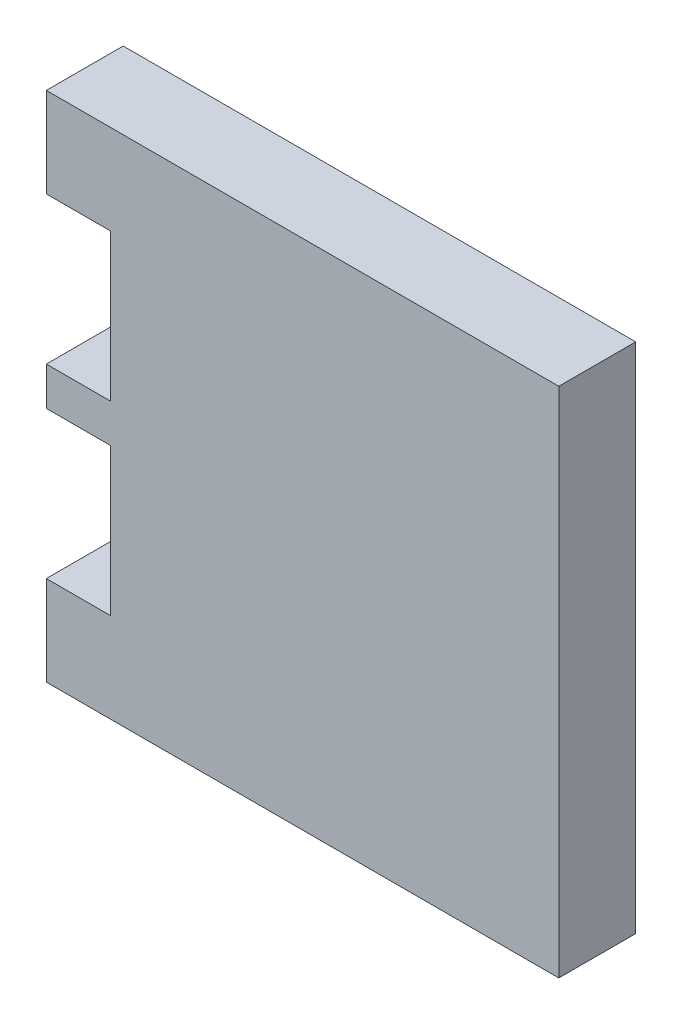
SolidWorks part; units mm, degrees
material "Plain Carbon Steel"
ref_plane "Front" through (0, 0, 0) normal (0, 0, 1) x (1, 0, 0)
ref_plane "Top" through (0, 0, 0) normal (0, 1, 0) x (1, 0, 0)
ref_plane "Right" through (0, 0, 0) normal (1, 0, 0) x (0, 0, -1)
sketch "Sketch1" plane through (0, 0, 0) normal (0, 0, 1) x (1, 0, 0)
  line L1 (-25.7556, 29.8071) -> (19.2444, 29.8071)
  line L2 (-25.7556, 29.8071) -> (-25.7556, -10.1929)
  line L3 (-25.7556, -10.1929) -> (19.2444, -10.1929)
  line L4 (19.2444, 29.8071) -> (19.2444, -10.1929)
  dimension "D1" = 45
  dimension "D2" = 40
extrude "Boss-Extrude1" add sketch "Sketch1" along normal blind 6 contours L2 L1 L4 L3
sketch "Sketch2" plane through (0, 0, 6) normal (0, 0, 1) x (1, 0, 0)
  line L0 (-25.7556, 29.8071) -> (-25.7556, -10.1929) construction
  line L1 (-25.7556, 29.8071) -> (-20.7556, 29.8071)
  line L2 (-25.7556, 29.8071) -> (-25.7556, 22.8071)
  line L3 (-25.7556, 22.8071) -> (-20.7556, 22.8071)
  line L4 (-20.7556, 29.8071) -> (-20.7556, 22.8071)
  line L5 (-25.7556, 22.8071) -> (-20.7556, 22.8071)
  line L6 (-25.7556, 22.8071) -> (-25.7556, 11.3071)
  line L7 (-25.7556, 11.3071) -> (-20.7556, 11.3071)
  line L8 (-20.7556, 22.8071) -> (-20.7556, 11.3071)
  line L9 (-25.7556, 8.3071) -> (-20.7556, 8.3071)
  line L10 (-25.7556, 8.3071) -> (-25.7556, -3.1929)
  line L11 (-25.7556, -3.1929) -> (-20.7556, -3.1929)
  line L12 (-20.7556, 8.3071) -> (-20.7556, -3.1929)
  line M4 (-25.7556, 29.8071) -> (-25.7556, -10.1929)
  dimension "D1" = 7
  dimension "D2" = 5
  dimension "D3" = 11.5
  dimension "D4" = 3
  dimension "D5" = 11.5
extrude "Cut-Extrude1" cut sketch "Sketch2" against normal blind 6 contours L8 L3 L7 M4 | L12 L9 L11 M4
sketch "Sketch3" plane through (0, 0, 6) normal (0, 0, 1) x (1, 0, 0)
  line L0 (19.2444, 29.8071) -> (19.2444, -10.1929) construction
  line L1 (19.2444, 29.8071) -> (14.2444, 29.8071)
  line L2 (19.2444, 29.8071) -> (19.2444, 20.8071)
  line L3 (19.2444, 20.8071) -> (14.2444, 20.8071)
  line L4 (14.2444, 29.8071) -> (14.2444, 20.8071)
  line L5 (19.2444, 11.3071) -> (14.2444, 11.3071)
  line L6 (19.2444, 11.3071) -> (19.2444, 8.3071)
  line L7 (19.2444, 8.3071) -> (14.2444, 8.3071)
  line L8 (14.2444, 11.3071) -> (14.2444, 8.3071)
  line L10 (19.2444, -10.1929) -> (14.2444, -10.1929)
  line L11 (19.2444, -10.1929) -> (19.2444, -1.1929)
  line L12 (19.2444, -1.1929) -> (14.2444, -1.1929)
  line L13 (14.2444, -10.1929) -> (14.2444, -1.1929)
  dimension "D1" = 5
  dimension "D2" = 9
  dimension "D3" = 9
  dimension "D4" = 3
  dimension "D5" = 9.5
extrude "Cut-Extrude3" cut sketch "Sketch3" against normal blind 6 contours L2 L1 L4 L3 | L6 L5 L8 L7 | L11 L10 L13 L12
sketch "Sketch4" plane through (0, 0, 6) normal (0, 0, 1) x (1, 0, 0)
  line L1 (14.2444, 29.8071) -> (22.7142, 29.8071)
  line L2 (14.2444, 29.8071) -> (14.2444, -11.0674)
  line L3 (14.2444, -11.0674) -> (22.7142, -11.0674)
  line L4 (22.7142, 29.8071) -> (22.7142, -11.0674)
extrude "Cut-Extrude4" cut sketch "Sketch4" against normal blind 6 contours L2 L1 L4 L3
